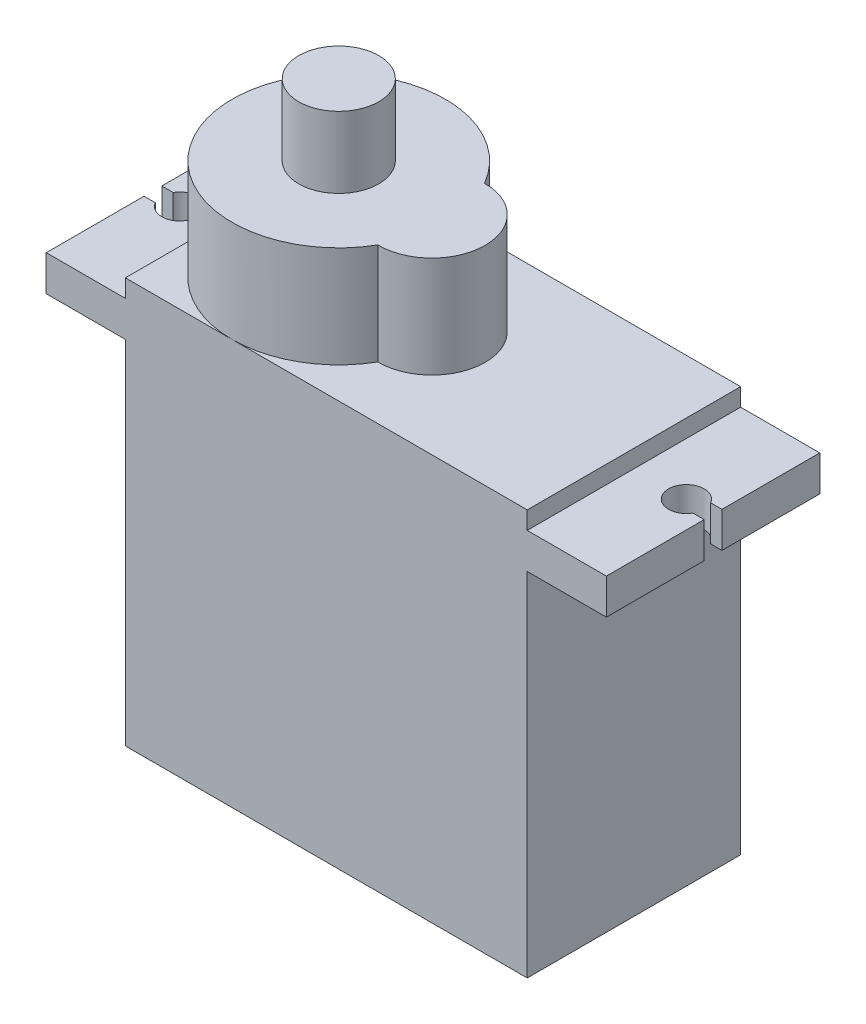
SolidWorks part; units mm, degrees
ref_plane "Piano frontale" through (0, 0, 0) normal (0, 0, 1) x (1, 0, 0)
ref_plane "Piano superiore" through (0, 0, 0) normal (0, 1, 0) x (1, 0, 0)
ref_plane "Piano destro" through (0, 0, 0) normal (1, 0, 0) x (0, 0, -1)
sketch "Schizzo1" plane through (0, 0, 0) normal (0, 1, 0) x (1, 0, 0)
  line L1 (0, 0) -> (22.6, 0)
  line L2 (0, 0) -> (0, 12)
  line L3 (0, 12) -> (22.6, 12)
  line L4 (22.6, 0) -> (22.6, 12)
  dimension "D1" = 22.6
  dimension "D2" = 12
extrude "Estrusione-Estrusione1" add sketch "Schizzo1" along normal blind 19.8
sketch "Schizzo3" plane through (0, 19.8, 0) normal (0, 1, 0) x (1, 0, 0)
  line L0 (-4.45, 0) -> (27.05, 0)
  line L1 (27.05, 0) -> (27.05, 12)
  line L2 (27.05, 12) -> (-4.45, 12)
  line L3 (-4.45, 12) -> (-4.45, 0)
  line L4 (0, 12) -> (0, 0) construction
  line L5 (22.6, 0) -> (22.6, 12) construction
  dimension "D1" = 4.45
  dimension "D2" = 4.45
  dimension "D3" = 12
extrude "Estrusione-Estrusione2" add sketch "Schizzo3" along normal blind 2 contours L3 L0 L1 L2
sketch "Schizzo4" plane through (0, 21.8, 0) normal (0, 1, 0) x (1, 0, 0)
  line L0 (27.05, 12) -> (-4.45, 12) construction
  line L1 (0, 0) -> (22.6, 0)
  line L2 (0, 0) -> (0, 12)
  line L3 (0, 12) -> (22.6, 12)
  line L4 (22.6, 0) -> (22.6, 12)
  line L6 (0, 12) -> (0, 0) construction
  dimension "D1" = 22.6
extrude "Estrusione-Estrusione3" add sketch "Schizzo4" along normal blind 1
sketch "Schizzo5" plane through (0, 22.8, 0) normal (0, 1, 0) x (1, 0, 0)
  line L0 (22.6, 12) -> (0, 12) construction
  line L1 (0, 12) -> (0, 0) construction
  circle A0 centre (6, 6) radius 6
  circle A1 centre (11.2364, 6) radius 3
  dimension "D1" = 6
  dimension "D2" = 6
  dimension "D4" = 12
  dimension "D3" = 5.2364
  dimension "D5" = 6
  dimension "D6" = 6
extrude "Estrusione-Estrusione4" add sketch "Schizzo5" along normal blind 5.7 contours A1 A0 | A0 A1 | A0 A1
sketch "Schizzo6" plane through (0, 28.5, 0) normal (0, 1, 0) x (1, 0, 0)
  circle A0 centre (6, 6) radius 2.25
  dimension "D1" = 4.5
extrude "Estrusione-Estrusione5" add sketch "Schizzo6" along normal blind 4
sketch "Schizzo7" plane through (0, 21.8, 0) normal (0, 1, 0) x (1, 0, 0)
  line L0 (27.05, 6) -> (-4.45, 6)
  line L1 (27.05, 0) -> (27.05, 12) construction
  line L2 (-4.45, 12) -> (-4.45, 0) construction
  line L4 (-4.45, 5.5) -> (-4.45, 6.5)
  line L5 (27.05, 5.5) -> (27.05, 6.5)
  line L6 (-4.45, 6.5) -> (-2.4491, 6.5)
  line L7 (-2.4491, 6.5) -> (-2.4491, 5.5)
  line L8 (-2.4491, 5.5) -> (-4.45, 5.5)
  line L9 (27.05, 6.5) -> (25.0476, 6.5)
  line L10 (25.0476, 6.5) -> (25.0476, 5.5)
  line L11 (25.0476, 5.5) -> (27.05, 5.5)
  circle A3 centre (-2.95, 6) radius 1
  circle A4 centre (25.55, 6) radius 1
  point P10 (-4.45, 6)
  point P12 (27.05, 6)
  line M3 (27.05, 0) -> (27.05, 12)
  dimension "D1" = 1
  dimension "D2" = 1
  dimension "D3" = 2
  dimension "D4" = 2
  dimension "D5" = 1.5
  dimension "D6" = 1.5
extrude "Taglio-Estrusione2" cut sketch "Schizzo7" against normal up to next contours A3 L0 L4 L8 | A3 L6 L4 L0 | L0 A3 L8 L7 | L0 A3 L6 L7 | L8 A3 L0 L7 | L6 A3 L0 L7 | L11 A4 L0 L10 | L0 A4 L11 L10 | L9 A4 L0 L10 | L0 A4 L9 L10 | A4 L0 L9 M3 | A4 L11 L0 M3
